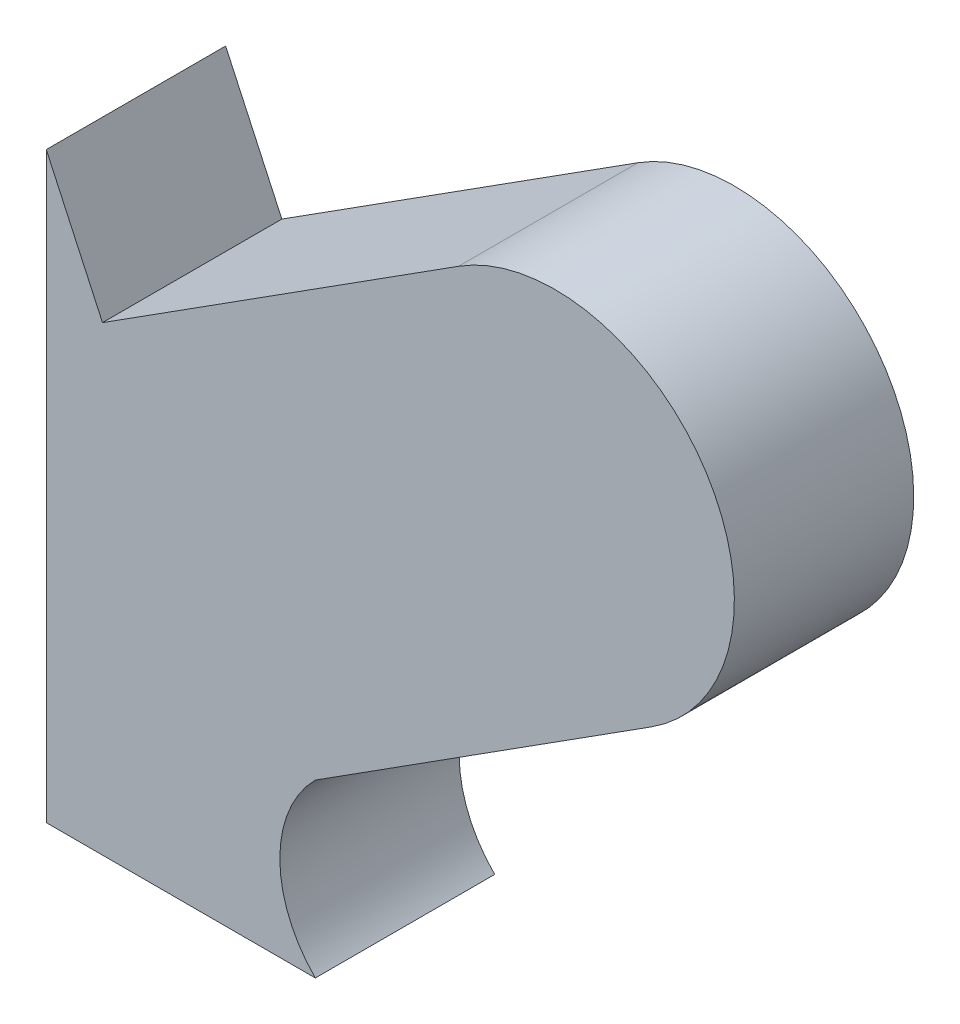
SolidWorks part; units mm, degrees
ref_plane "Front Plane" through (0, 0, 0) normal (0, 0, 1) x (1, 0, 0)
ref_plane "Top Plane" through (0, 0, 0) normal (0, 1, 0) x (1, 0, 0)
ref_plane "Right Plane" through (0, 0, 0) normal (1, 0, 0) x (0, 0, -1)
sketch "Sketch1" plane through (0, 0, 0) normal (0, 0, 1) x (1, 0, 0)
  line L0 (0, 0) -> (0, 32.5)
  line L1 (0, 0) -> (15, 0)
  line L2 (0, 32.5) -> (3.1338, 25.7102)
  line L3 (15, 9.5561) -> (33.7357, 21.492)
  line L5 (22.9897, 38.3598) -> (3.1338, 25.7102)
  arc A0 (22.9897, 38.3598) -> (33.7357, 21.492) centre (28.3627, 29.9259) cw
  arc A1 (15, 0) -> (15, 9.5561) centre (19.778, 4.778) cw
  dimension "D1" = 32.5
  dimension "D2" = 15
  dimension "D3" = 32.5
  dimension "D4" = 40
  dimension "D6" = 20
extrude "Boss-Extrude1" add sketch "Sketch1" along normal blind 10
